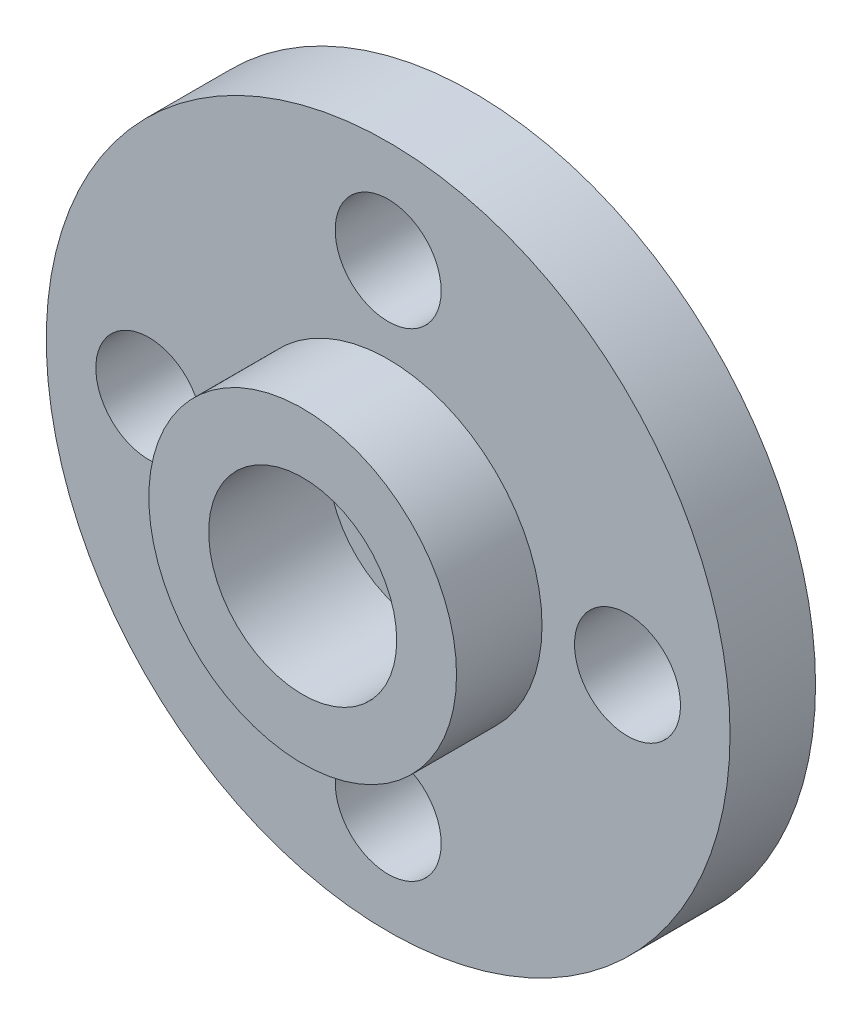
SolidWorks part; units mm, degrees
ref_plane "Front Plane" through (0, 0, 0) normal (1, 0, 0) x (0, 1, 0)
ref_plane "Top Plane" through (0, 0, 0) normal (0, 0, 1) x (0, 1, 0)
ref_plane "Right Plane" through (0, 0, 0) normal (0, 1, 0) x (-1, 0, 0)
sketch "Sketch1" plane through (0, 0, 0) normal (0, 0, 1) x (0, 1, 0)
  circle A0 centre (0, 0) radius 10
  dimension "D1" = 20
extrude "Boss-Extrude1" add sketch "Sketch1" along normal blind 2.5
sketch "Sketch2" plane through (0, 0, 2.5) normal (0, 0, 1) x (1, 0, 0)
  circle A0 centre (0, 0) radius 4.5
  dimension "D1" = 9
extrude "Extrude-Thin1" add sketch "Sketch2" along normal blind 2.5 thin thin type one direction reverse wall 1.75
sketch "Sketch3" plane through (0, 0, 2.5) normal (0, 0, 1) x (1, 0, 0)
  circle A0 centre (0, 0) radius 1.55
  circle A1 centre (7, 0) radius 1.55
  circle A2 centre (0, 7) radius 1.55
  circle A3 centre (-7, 0) radius 1.55
  circle A4 centre (0, -7) radius 1.55
  circle A5 centre (0, 0) radius 10 construction
  point P14 (0, 0)
  point P15 (0, 0)
  point P16 (0, 0)
  point P17 (0, 0)
  dimension "D1" = 3.1
  dimension "D2" = 7
  dimension "D3" = 7
  dimension "D4" = 7
  dimension "D5" = 7
extrude "Cut-Extrude1" cut sketch "Sketch3" against normal through all both and the other way through all
sketch "Sketch4" plane through (0, 0, 2.5) normal (0, 0, 1) x (1, 0, 0)
  circle A0 centre (0, 0) radius 2.75
  circle A1 centre (0, 0) radius 2.75 construction
extrude "Cut-Extrude2" cut sketch "Sketch4" against normal blind 1
